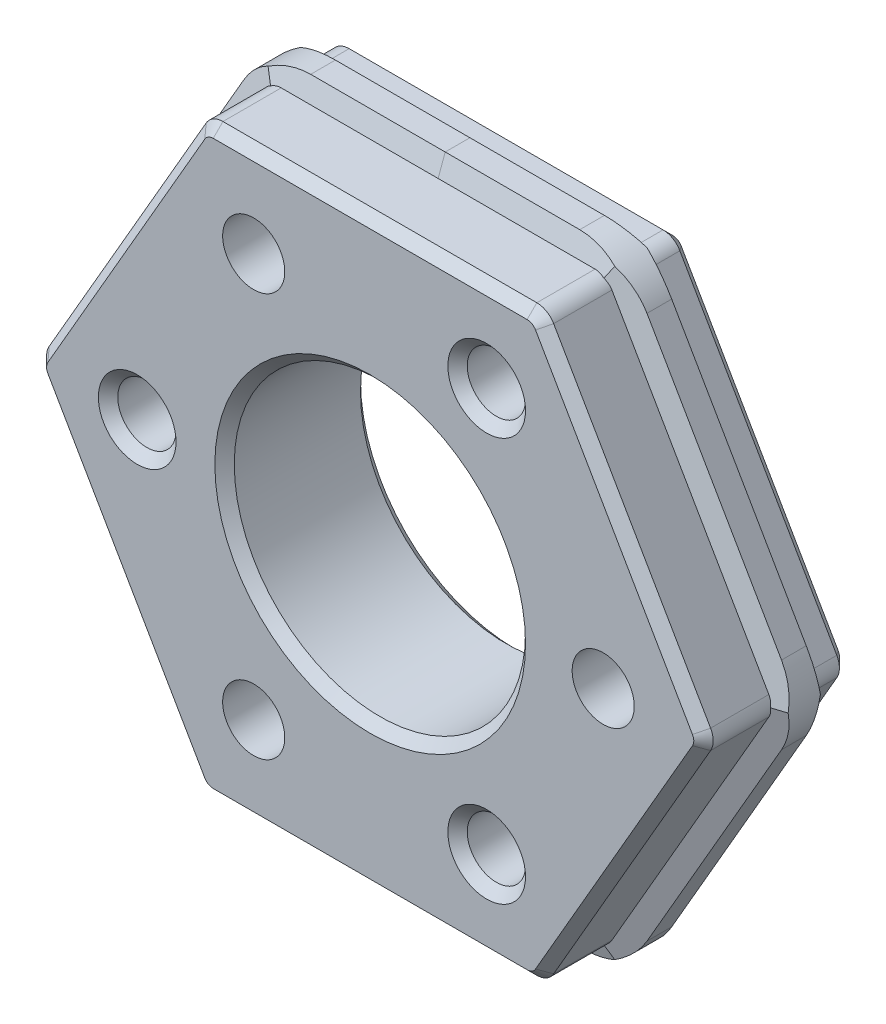
SolidWorks part; units mm, degrees
material "6061 合金"
ref_plane "前视基准面" through (0, 0, 0) normal (0, 0, 1) x (1, 0, 0)
ref_plane "上视基准面" through (0, 0, 0) normal (0, 1, 0) x (1, 0, 0)
ref_plane "右视基准面" through (0, 0, 0) normal (1, 0, 0) x (0, 0, -1)
other "Configuration Table"
sketch "草图1" plane through (0, 0, 0) normal (0, 0, 1) x (1, 0, 0)
  line L1 (-16, 16) -> (16, 16)
  line L2 (-16, 16) -> (-16, -16)
  line L3 (-16, -16) -> (16, -16)
  line L4 (16, 16) -> (16, -16)
  line L5 (0, -16) -> (0, 16) construction
  line L6 (-16, 0) -> (16, 0) construction
  circle A0 centre (0, 0) radius 7.5
  circle A1 centre (0, 0) radius 18 construction
  circle A2 centre (0, 0) radius 12 construction
  dimension "D1" = 36
  dimension "D2" = 15
  dimension "D3" = 24
  dimension "D6" = 32
  dimension "D7" = 32
extrude "凸台-拉伸1" add sketch "草图1" along normal mid plane 6
sketch "草图23" plane through (0, 0, 3) normal (0, 0, 1) x (1, 0, 0)
  line L0 (16, 16) -> (16, -16)
  line L8 (-16, -16) -> (16, -16)
  line L11 (16, -16) -> (16, 16)
  line L12 (16, -16) -> (16, 16)
  line L14 (16, 16) -> (-16, 16)
  line L15 (-16, 16) -> (-16, -16)
  line L16 (-16, -16) -> (16, -16)
  line L22 (16, 16) -> (-16, 16)
  line L23 (-16, 16) -> (-16, -16)
  line M23 (-16, -16) -> (16, -16)
  line M25 (16, -16) -> (16, 16)
  line M35 (16, 16) -> (-16, 16)
  line M37 (-16, 16) -> (-16, -16)
  circle M39 centre (0, 0) radius 7.5
  dimension "D1" = 0
extrude "凸台-拉伸4" add sketch "草图23" along normal blind 1.5 contours M23 M25 M35 M37 M39
sketch "草图8" plane through (0, 0, -3) normal (0, 0, -1) x (-1, 0, 0)
  circle A0 centre (0, 0) radius 12 construction
  point P0 (-12, 0)
  point P1 (6, 10.3923)
  point P9 (6, -10.3923)
  dimension "D1" = 24
  dimension "D2" = 3
hole_wizard "M3 六角圆柱头螺钉的柱形沉头孔1" positions "草图8" profile "草图9" counterbore size "M3" standard "GB" end condition through all
sketch "草图9" plane through (12, 0, -3) normal (1, 0, 0) x (0, 1, 0)
  line L0 (0, 0) -> (0, 7.5)
  line L1 (0, 7.5) -> (1.6, 7.5)
  line L3 (1.6, 7.5) -> (1.6, 5)
  line L4 (1.6, 5) -> (2.85, 5)
  line L5 (2.85, 5) -> (2.85, 0)
  line L7 (2.85, 0) -> (0, 0)
  line L11 (0, -6.35) -> (0, 107.95) construction
  dimension "通孔孔直径" = 3.2
  dimension "通孔孔深度" = 7.5
  dimension "柱形沉头孔直径" = 5.7
  dimension "柱形沉头孔深度" = 5
sketch "草图24" plane through (0, 0, 4.5) normal (0, 0, 1) x (1, 0, 0)
  circle A0 centre (0, 0) radius 12 construction
  point P0 (-12, 0)
  point P13 (6, 10.3923)
  point P14 (6, -10.3923)
  dimension "D1" = 24
  dimension "D2" = 3
hole_wizard "Ø3.0mm 暗销孔1" positions "草图24" profile "草图25" hole size "Ø3.0" standard "BSI"
sketch "草图25" plane through (-12, 0, 4.5) normal (1, 0, 0) x (0, -1, 0)
  line L0 (0, 0) -> (0, 4.9013)
  line L1 (0, 4.9013) -> (1.5, 4)
  line L2 (1.5, 4) -> (1.5, 0)
  line L5 (1.5, 0) -> (0, 0)
  line L10 (0, 4.9013) -> (-1.5, 4) construction
  line L11 (0, -6.35) -> (0, 107.95) construction
  dimension "孔直径" = 3
  dimension "孔深度" = 4
  dimension "导头角度" = 118
ref_plane "基准面1" through (0, 0, 0) normal (0, 0, -1) x (-1, 0, 0)
sketch "草图26" plane through (0, 0, -3) normal (0, 0, -1) x (-1, 0, 0)
  circle A0 centre (0, 0) radius 15
  dimension "D1" = 30
extrude "切除-拉伸1" cut sketch "草图26" against normal through all flip side to cut
sketch "草图35" plane through (0, 0, 4.5) normal (0, 0, 1) x (1, 0, 0)
  line L0 (-18.5745, 0) -> (16.9837, 0) construction
ref_plane "基准面2" through (0, 0, 0) normal (0, -1, 0) x (1, 0, 0)
sketch "草图42" plane through (0, 0, -3) normal (0, 0, -1) x (-1, 0, 0)
  line L9 (-17.3205, 0) -> (-8.6603, -15)
  line L10 (-8.6603, -15) -> (8.6603, -15)
  line L11 (8.6603, -15) -> (17.3205, 0)
  line L12 (17.3205, 0) -> (8.6603, 15)
  line L13 (8.6603, 15) -> (-8.6603, 15)
  line L14 (-8.6603, 15) -> (-17.3205, 0)
  circle A0 centre (0, 0) radius 15 construction
  circle A2 centre (0, 0) radius 15
  circle A3 centre (0, 0) radius 15 construction
extrude "凸台-拉伸5" add sketch "草图42" against normal up to surface (7.5 mm away)
sketch "草图43" plane through (0, 0, 0) normal (1, 0, 0) x (0, 0, -1)
  line L1 (-1, 15) -> (1, 15)
  line L3 (1, 15) -> (0.636, 16)
  line L4 (0.636, 16) -> (-0.636, 16)
  line L5 (-0.636, 16) -> (-1, 15)
  line L6 (-4.5, 15) -> (3, 15) construction
  line L9 (0, 22.7244) -> (0, -9.6288) construction
  dimension "D1" = 2
  dimension "D2" = 40
  dimension "D3" = 1
ref_plane "基准面3" through (0, 0, -1) normal (0, 0, -1) x (-1, 0, 0)
sketch "草图44" plane through (0, 0, -1) normal (0, 0, -1) x (-1, 0, 0)
  line L6 (-8.6603, 15) -> (-17.3205, 0)
  line L7 (-8.6603, 15) -> (-17.3205, 0)
  line L8 (8.6603, 15) -> (-8.6603, 15)
  line L9 (8.6603, 15) -> (-8.6603, 15)
  line L11 (-17.3205, 0) -> (-8.6603, -15)
  line L12 (-8.6603, -15) -> (8.6603, -15)
  line L13 (8.6603, -15) -> (17.3205, 0)
  line L14 (17.3205, 0) -> (8.6603, 15)
  line L19 (-17.3205, 0) -> (-8.6603, -15)
  line L20 (-8.6603, -15) -> (8.6603, -15)
  line L21 (8.6603, -15) -> (17.3205, 0)
  line L22 (17.3205, 0) -> (8.6603, 15)
  dimension "D1" = 0
sweep "扫描1" add profiles "草图43" path "草图44"
fillet "圆角1" radius 1 12 edges at (8.6603, -15, 2.75) (-8.6603, -15, 2.75) (-17.3205, 0, 2.75) (8.6603, -15, -2) (-8.6603, -15, -2) (-17.3205, 0, -2) (8.6603, 15, 2.75) (8.6603, 15, -2) (17.3205, 0, 2.75) (17.3205, 0, -2) (-8.6603, 15, 2.75) (-8.6603, 15, -2)
chamfer "倒角1" distance 0.5 angle 45 29 edges at (12.9904, -7.5, -3) (8.5829, -14.866, -3) (0, -15, -3) (-8.5829, -14.866, -3) (-12.9904, -7.5, -3) (-17.1658, 0, -3) (-12.9904, 7.5, -3) (12.9904, -7.5, 4.5) (8.5829, -14.866, 4.5) (0, -15, 4.5) (-8.5829, -14.866, 4.5) (-12.9904, -7.5, 4.5) (-17.1658, 0, 4.5) (-12.9904, 7.5, 4.5) (7.5, 0, 4.5) (7.5, 0, -3) (17.1658, 0, 4.5) (12.9904, 7.5, 4.5) (-8.5829, 14.866, 4.5) (8.5829, 14.866, 4.5) (0, 15, 4.5) (17.1658, 0, -3) (12.9904, 7.5, -3) (-8.5829, 14.866, -3) (8.5829, 14.866, -3) (0, 15, -3) (7.5, -10.3923, 4.5) (7.5, 10.3923, 4.5) (-10.5, 0, 4.5)
fillet "圆角2" radius 4 6 edges at (-9.2376, -16, 0) (9.2376, -16, 0) (18.4752, 0, 0) (9.2376, 16, 0) (-9.2376, 16, 0) (-18.4752, 0, 0)
